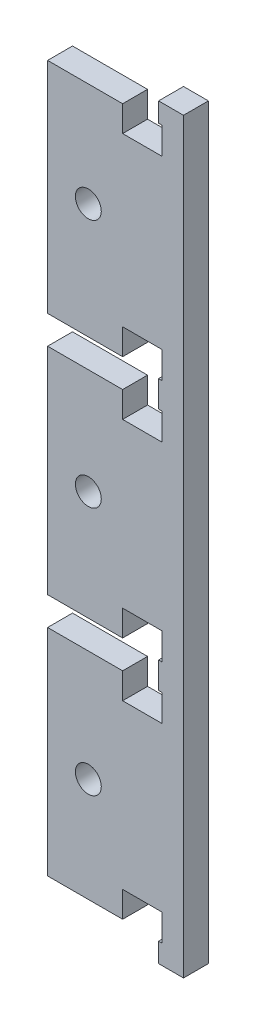
SolidWorks part; units mm, degrees
material "AISI 4130 Steel, annealed at 865C"
ref_plane "X-Y Datum" through (0, 0, 0) normal (0, 0, 1) x (1, 0, 0)
ref_plane "X-Z Datum" through (0, 0, 0) normal (0, 1, 0) x (1, 0, 0)
ref_plane "Y-Z Datum" through (0, 0, 0) normal (1, 0, 0) x (0, 0, -1)
sketch "Sketch2" plane through (0, 0, 0) normal (0, 0, 1) x (1, 0, 0)
  line L0 (-332.3254, 135.7857) -> (-332.3254, 326.2217) construction
  line L1 (-316.4504, 135.7857) -> (-348.2004, 135.7857) construction
  line L2 (-316.4504, 326.2217) -> (-348.2004, 326.2217) construction
  line L4 (-348.2004, 135.7857) -> (-308.0684, 135.7857)
  line L5 (-348.2004, 135.7857) -> (-348.2004, 326.2217)
  line L6 (-348.2004, 326.2217) -> (-308.0684, 326.2217)
  line L7 (-308.0684, 135.7857) -> (-308.0684, 326.2217)
  dimension "D1" = 40.132
extrude "Boss-Extrude1" add sketch "Sketch2" along normal blind 6.35
sketch "Sketch3" plane through (0, 0, 6.35) normal (0, 0, 1) x (1, 0, 0)
  line L0 (-316.4504, 326.2217) -> (-348.2004, 326.2217) construction
  line L1 (-348.2004, 326.2217) -> (-348.2004, 323.0467) construction
  line L2 (-348.2004, 323.0467) -> (-316.4504, 323.0467) construction
  line L3 (-316.4504, 323.0467) -> (-316.4504, 326.2217) construction
  line L4 (-316.4504, 259.9597) -> (-316.4504, 263.1347) construction
  line L5 (-316.4504, 263.1347) -> (-348.2004, 263.1347) construction
  line L6 (-348.2004, 263.1347) -> (-348.2004, 259.9597) construction
  line L7 (-348.2004, 259.9597) -> (-316.4504, 259.9597) construction
  line L8 (-316.4504, 197.8727) -> (-316.4504, 201.0477) construction
  line L9 (-316.4504, 201.0477) -> (-348.2004, 201.0477) construction
  line L10 (-348.2004, 201.0477) -> (-348.2004, 197.8727) construction
  line L11 (-348.2004, 197.8727) -> (-316.4504, 197.8727) construction
  line L12 (-316.4504, 135.7857) -> (-316.4504, 138.9607) construction
  line L13 (-316.4504, 138.9607) -> (-348.2004, 138.9607) construction
  line L14 (-348.2004, 138.9607) -> (-348.2004, 135.7857) construction
  line L15 (-348.2004, 135.7857) -> (-316.4504, 135.7857) construction
  line L16 (-316.4504, 326.2217) -> (-348.2004, 326.2217) construction
  line L17 (-348.2004, 326.2217) -> (-348.2004, 323.0467) construction
  line L18 (-348.2004, 323.0467) -> (-316.4504, 323.0467) construction
  line L19 (-316.4504, 323.0467) -> (-316.4504, 326.2217) construction
  line L20 (-316.4504, 259.9597) -> (-316.4504, 263.1347) construction
  line L21 (-316.4504, 263.1347) -> (-348.2004, 263.1347) construction
  line L22 (-348.2004, 263.1347) -> (-348.2004, 259.9597) construction
  line L23 (-348.2004, 259.9597) -> (-316.4504, 259.9597) construction
  line L24 (-316.4504, 197.8727) -> (-316.4504, 201.0477)
  line L25 (-316.4504, 201.0477) -> (-348.2004, 201.0477) construction
  line L26 (-348.2004, 201.0477) -> (-348.2004, 197.8727) construction
  line L27 (-348.2004, 197.8727) -> (-316.4504, 197.8727) construction
  line L28 (-316.4504, 135.7857) -> (-316.4504, 138.9607) construction
  line L29 (-316.4504, 138.9607) -> (-348.2004, 138.9607) construction
  line L30 (-348.2004, 138.9607) -> (-348.2004, 135.7857) construction
  line L31 (-348.2004, 135.7857) -> (-316.4504, 135.7857) construction
  line L32 (-314.4184, 140.9927) -> (-350.2324, 140.9927)
  line L33 (-350.2324, 140.9927) -> (-350.2324, 133.7537)
  line L34 (-350.2324, 133.7537) -> (-314.4184, 133.7537)
  line L35 (-314.4184, 133.7537) -> (-314.4184, 140.9927)
  line L36 (-314.4184, 203.0797) -> (-350.2324, 203.0797)
  line L37 (-350.2324, 203.0797) -> (-350.2324, 195.8407)
  line L38 (-350.2324, 195.8407) -> (-314.4184, 195.8407)
  line L39 (-314.4184, 195.8407) -> (-314.4184, 203.0797)
  line L40 (-314.4184, 265.1667) -> (-350.2324, 265.1667)
  line L41 (-350.2324, 265.1667) -> (-350.2324, 257.9277)
  line L42 (-350.2324, 257.9277) -> (-314.4184, 257.9277)
  line L43 (-314.4184, 257.9277) -> (-314.4184, 265.1667)
  line L44 (-350.2324, 321.0147) -> (-314.4184, 321.0147)
  line L45 (-314.4184, 321.0147) -> (-314.4184, 328.2537)
  line L46 (-314.4184, 328.2537) -> (-350.2324, 328.2537)
  line L47 (-350.2324, 328.2537) -> (-350.2324, 321.0147)
  line L50 (-342.7084, 326.2217) -> (-342.7084, 135.7857)
  line L51 (-342.7084, 326.2217) -> (-342.7084, 135.7857)
  circle A0 centre (-332.3254, 294.5357) radius 3.3 construction
  circle A1 centre (-332.3254, 231.0357) radius 3.3 construction
  circle A2 centre (-332.3254, 167.5357) radius 3.3 construction
  circle A3 centre (-332.3254, 294.5357) radius 3.3
  circle A4 centre (-332.3254, 231.0357) radius 3.3
  circle A5 centre (-332.3254, 167.5357) radius 3.3
  line M12 (-348.2004, 326.2217) -> (-348.2004, 135.7857)
  line M13 (-348.2004, 135.7857) -> (-308.0684, 135.7857)
  line M15 (-308.0684, 326.2217) -> (-348.2004, 326.2217)
  dimension "D1" = 2.032
  dimension "D2" = 5.492
extrude "Cut-Extrude1" cut sketch "Sketch3" against normal through all contours L35 L32 L29 L28 M13 M12 | L34 L35 L32 L33 M13 M12 | L28 L29 M12 M13 | L27 L24 L25 M12 | L38 L39 L36 L25 L24 L27 M12 | L23 L20 L21 M12 | L42 L43 L40 L21 L20 L23 M12 | L18 L19 M15 M12 | L44 L45 L19 L18 M15 M12 | L46 L47 L44 L45 M12 M15 | L41 L42 L40 M12 | L37 L38 L36 M12 | A5 | A4 | A3 | L51 L38 L32 M12 | L51 L42 L36 M12 | L51 L44 L40 M12
sketch "Sketch4" plane through (0, 0, 6.35) normal (0, 0, 1) x (1, 0, 0)
  line L0 (-313.8025, 140.9927) -> (-313.8025, 147.3427) construction
  line L1 (-323.3275, 140.9927) -> (-323.3275, 147.3427) construction
  line L2 (-313.8025, 189.4813) -> (-313.8025, 195.8313) construction
  line L3 (-323.3275, 189.4813) -> (-323.3275, 195.8313) construction
  line L4 (-313.8025, 203.0703) -> (-313.8025, 209.4203) construction
  line L5 (-323.3275, 203.0703) -> (-323.3275, 209.4203) construction
  line L6 (-313.8025, 251.5843) -> (-313.8025, 257.9343) construction
  line L7 (-323.3275, 251.5843) -> (-323.3275, 257.9343) construction
  line L8 (-323.3275, 265.1733) -> (-323.3275, 271.5233) construction
  line L9 (-313.8025, 265.1733) -> (-313.8025, 271.5233) construction
  line L10 (-323.3275, 314.6779) -> (-323.3275, 321.0279) construction
  line L11 (-313.8025, 314.6779) -> (-313.8025, 321.0279) construction
  line L12 (-313.8025, 140.9927) -> (-313.8025, 147.3427) construction
  line L13 (-323.3275, 140.9927) -> (-323.3275, 147.3427) construction
  line L14 (-313.8025, 189.4813) -> (-313.8025, 195.8313) construction
  line L15 (-323.3275, 189.4813) -> (-323.3275, 195.8313) construction
  line L16 (-313.8025, 203.0703) -> (-313.8025, 209.4203) construction
  line L17 (-323.3275, 203.0703) -> (-323.3275, 209.4203) construction
  line L18 (-313.8025, 251.5843) -> (-313.8025, 257.9343) construction
  line L19 (-323.3275, 251.5843) -> (-323.3275, 257.9343) construction
  line L20 (-323.3275, 265.1733) -> (-323.3275, 271.5233) construction
  line L21 (-313.8025, 265.1733) -> (-313.8025, 271.5233) construction
  line L22 (-323.3275, 314.6779) -> (-323.3275, 321.0279) construction
  line L23 (-313.8025, 314.6779) -> (-313.8025, 321.0279) construction
  line L24 (-333.1834, 314.6779) -> (-288.5206, 314.6779) construction
  line L25 (-288.5206, 321.0279) -> (-333.1834, 321.0279) construction
  line L26 (-333.1834, 140.9927) -> (-288.5206, 140.9927) construction
  line L27 (-288.5206, 147.3427) -> (-333.1834, 147.3427) construction
  line L28 (-333.1834, 189.4813) -> (-288.5206, 189.4813) construction
  line L29 (-288.5206, 195.8313) -> (-333.1834, 195.8313) construction
  line L30 (-333.1834, 203.0703) -> (-288.5206, 203.0703) construction
  line L31 (-288.5206, 209.4203) -> (-333.1834, 209.4203) construction
  line L32 (-333.1834, 251.5843) -> (-288.5206, 251.5843) construction
  line L33 (-288.5206, 257.9343) -> (-333.1834, 257.9343) construction
  line L34 (-333.1834, 265.1733) -> (-288.5206, 265.1733) construction
  line L35 (-288.5206, 271.5233) -> (-333.1834, 271.5233) construction
  line L36 (-323.3275, 140.9927) -> (-313.8025, 140.9927) construction
  line L37 (-313.8025, 147.3427) -> (-323.3275, 147.3427) construction
  line L38 (-323.3275, 189.4813) -> (-313.8025, 189.4813) construction
  line L39 (-313.8025, 195.8313) -> (-323.3275, 195.8313) construction
  line L40 (-323.3275, 203.0703) -> (-313.8025, 203.0703) construction
  line L41 (-313.8025, 209.4203) -> (-323.3275, 209.4203) construction
  line L42 (-323.3275, 251.5843) -> (-313.8025, 251.5843) construction
  line L43 (-313.8025, 257.9343) -> (-323.3275, 257.9343) construction
  line L44 (-323.3275, 265.1733) -> (-313.8025, 265.1733) construction
  line L45 (-313.8025, 271.5233) -> (-323.3275, 271.5233) construction
  line L46 (-313.8025, 321.0279) -> (-323.3275, 321.0279) construction
  line L47 (-323.3275, 314.6779) -> (-313.8025, 314.6779) construction
  line L48 (-313.5485, 140.7387) -> (-313.5485, 147.5967)
  line L49 (-313.5485, 147.5967) -> (-323.5815, 147.5967)
  line L50 (-323.5815, 140.7387) -> (-323.5815, 147.5967)
  line L51 (-323.5815, 140.7387) -> (-313.5485, 140.7387)
  line L52 (-313.5485, 189.2273) -> (-313.5485, 196.0853)
  line L53 (-313.5485, 196.0853) -> (-323.5815, 196.0853)
  line L54 (-323.5815, 189.2273) -> (-323.5815, 196.0853)
  line L55 (-323.5815, 189.2273) -> (-313.5485, 189.2273)
  line L56 (-313.5485, 202.8163) -> (-313.5485, 209.6743)
  line L57 (-313.5485, 209.6743) -> (-323.5815, 209.6743)
  line L58 (-323.5815, 202.8163) -> (-323.5815, 209.6743)
  line L59 (-323.5815, 202.8163) -> (-313.5485, 202.8163)
  line L60 (-313.5485, 251.3303) -> (-313.5485, 258.1883)
  line L61 (-313.5485, 258.1883) -> (-323.5815, 258.1883)
  line L62 (-323.5815, 251.3303) -> (-323.5815, 258.1883)
  line L63 (-323.5815, 251.3303) -> (-313.5485, 251.3303)
  line L64 (-323.5815, 264.9193) -> (-323.5815, 271.7773)
  line L65 (-313.5485, 271.7773) -> (-323.5815, 271.7773)
  line L66 (-313.5485, 264.9193) -> (-313.5485, 271.7773)
  line L67 (-323.5815, 264.9193) -> (-313.5485, 264.9193)
  line L68 (-323.5815, 314.4239) -> (-323.5815, 321.2819)
  line L69 (-313.5485, 321.2819) -> (-323.5815, 321.2819)
  line L70 (-313.5485, 314.4239) -> (-313.5485, 321.2819)
  line L71 (-323.5815, 314.4239) -> (-313.5485, 314.4239)
  line M4 (-342.7084, 140.9927) -> (-314.4184, 140.9927)
  line M9 (-314.4184, 326.2217) -> (-314.4184, 321.0147)
  line M10 (-314.4184, 321.0147) -> (-342.7084, 321.0147)
  line M13 (-314.4184, 265.1667) -> (-314.4184, 257.9277)
  line M14 (-314.4184, 257.9277) -> (-342.7084, 257.9277)
  line M16 (-342.7084, 203.0797) -> (-314.4184, 203.0797)
  line M17 (-314.4184, 203.0797) -> (-314.4184, 195.8407)
  dimension "D1" = 0.254
extrude "Cut-Extrude2" cut sketch "Sketch4" against normal through all contours L12 L37 L13 L36 M4 | L14 L39 L15 L38 | L16 L41 L17 L40 M16 M17 | L18 L43 L19 L42 M13 M14 | L21 L45 L20 L44 | L22 L47 L23 L46 M9 M10
